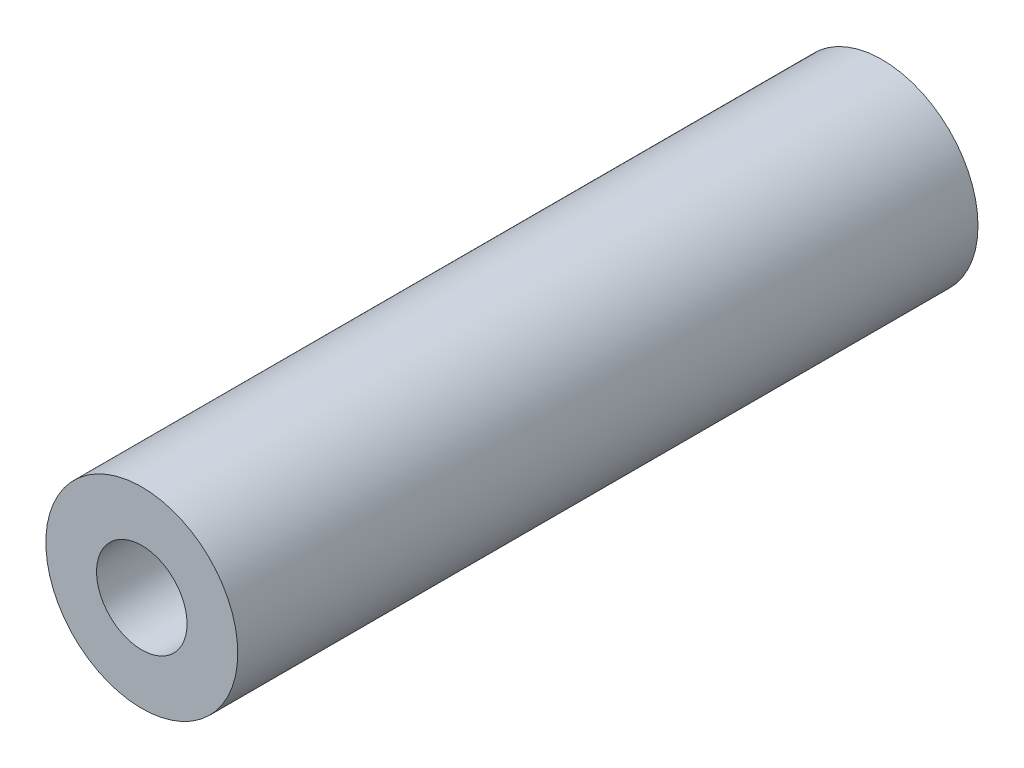
SolidWorks part; units mm, degrees
ref_plane "前视基准面" through (0, 0, 0) normal (0, 0, 1) x (1, 0, 0)
ref_plane "上视基准面" through (0, 0, 0) normal (0, 1, 0) x (1, 0, 0)
ref_plane "右视基准面" through (0, 0, 0) normal (1, 0, 0) x (0, 0, -1)
sketch "草图1" plane through (0, 0, 0) normal (0, 0, 1) x (1, 0, 0)
  circle A0 centre (0, 0) radius 1.65
  circle A1 centre (0, 0) radius 3.5
  dimension "D1" = 3.3
  dimension "D2" = 7
extrude "凸台-拉伸1" add sketch "草图1" along normal blind 27
